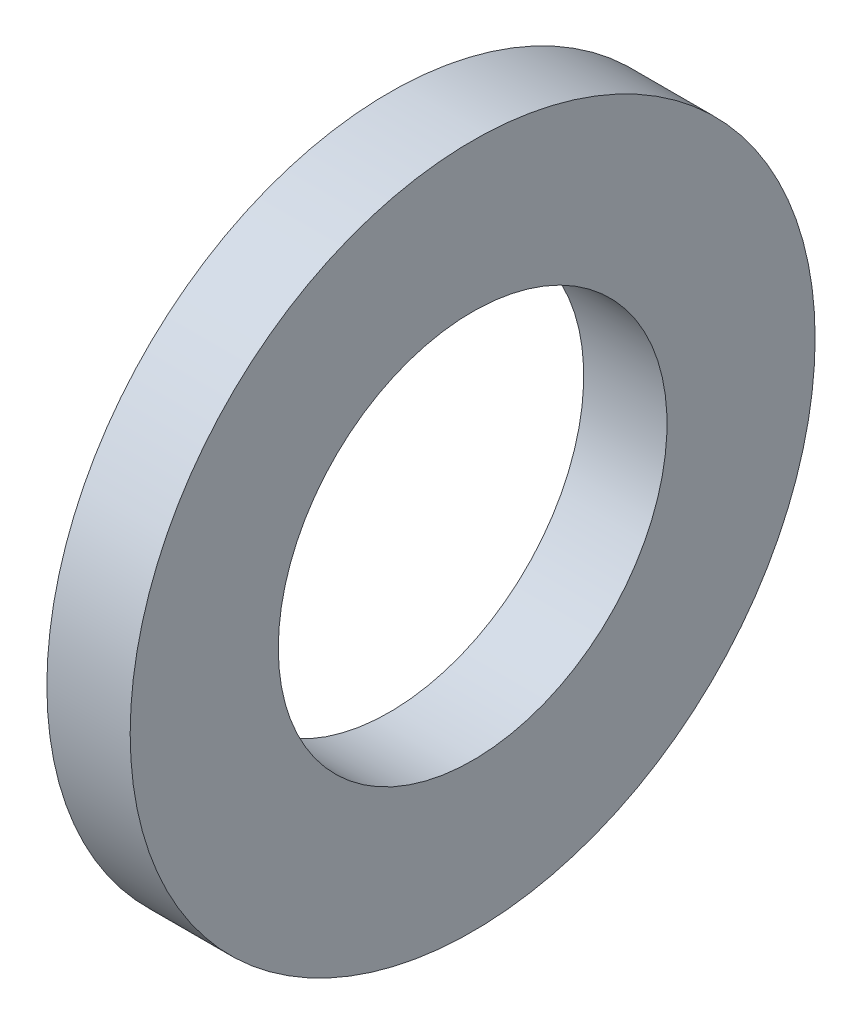
SolidWorks part; units mm, degrees
ref_plane "Plane1" through (0, 0, 0) normal (0, 0, 1) x (1, 0, 0)
ref_plane "Plane2" through (0, 0, 0) normal (0, 1, 0) x (1, 0, 0)
ref_plane "Plane3" through (0, 0, 0) normal (1, 0, 0) x (0, 0, -1)
sketch "Sketch1" plane through (0, 0, 0) normal (0, 0, 1) x (1, 0, 0)
  line L0 (-34.925, 0) -> (9.525, 0) construction
  line L1 (0, 10.5) -> (0, 18.5)
  line L2 (0, 18.5) -> (-4.5, 18.5)
  line L3 (-4.5, 18.5) -> (-4.5, 10.5)
  line L4 (-4.5, 10.5) -> (0, 10.5)
  dimension "Thickness" = 4.5
  dimension "Inside_dia" = 21
  dimension "Outside_dia" = 37
revolve "Base-Revolve" add sketch "Sketch1" angle 360 about L0
